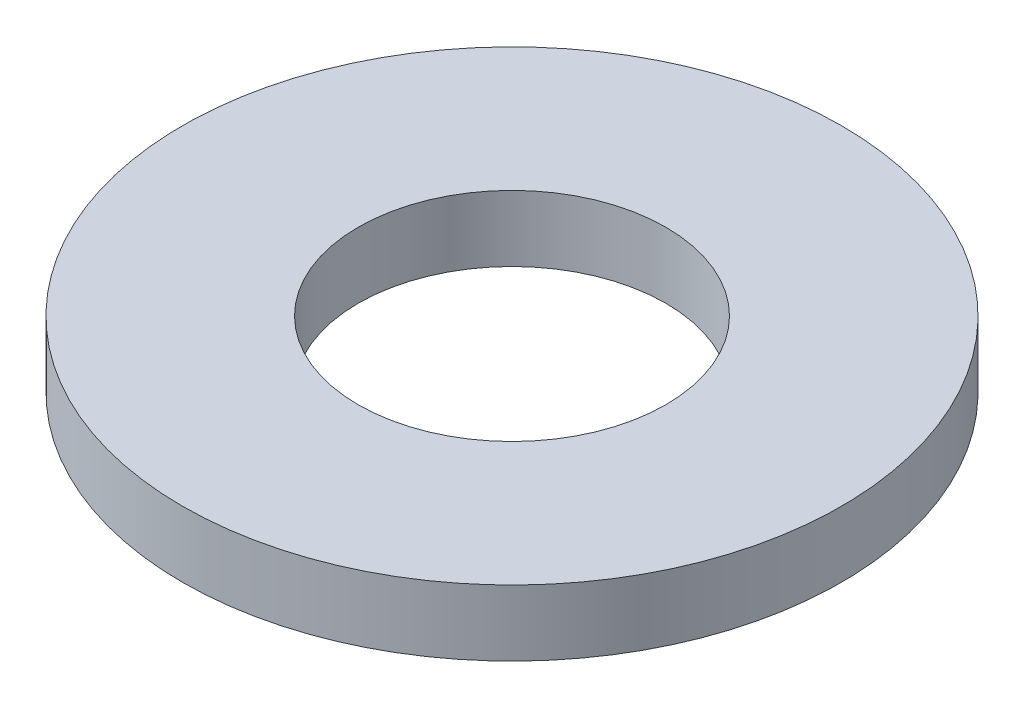
SolidWorks part; units mm, degrees
ref_plane "Front Plane" through (0, 0, 0) normal (0, 0, 1) x (1, 0, 0)
ref_plane "Top Plane" through (0, 0, 0) normal (0, 1, 0) x (1, 0, 0)
ref_plane "Right Plane" through (0, 0, 0) normal (1, 0, 0) x (0, 0, -1)
sketch "Sketch1" plane through (0, 0, 0) normal (0, 1, 0) x (1, 0, 0)
  circle A0 centre (0, 0) radius 3.75
  circle A1 centre (0, 0) radius 1.75
  dimension "D1" = 7.5
  dimension "D2" = 3.5
extrude "Boss-Extrude1" add sketch "Sketch1" along normal blind 0.75
